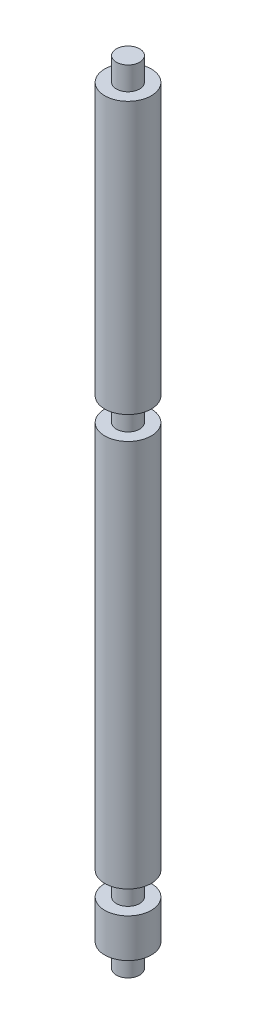
SolidWorks part; units mm, degrees
material "Cast Alloy Steel"
ref_plane "Front Plane" through (0, 0, 0) normal (0, 0, 1) x (1, 0, 0)
ref_plane "Top Plane" through (0, 0, 0) normal (0, 1, 0) x (1, 0, 0)
ref_plane "Right Plane" through (0, 0, 0) normal (1, 0, 0) x (0, 0, -1)
sketch "Sketch1" plane through (0, 0, 0) normal (1, 0, 0) x (0, 0, -1)
  line L0 (0, 102) -> (1.5, 102)
  line L1 (1.5, 102) -> (1.5, 99)
  line L2 (1.5, 99) -> (3, 99)
  line L3 (3, 99) -> (3, 64)
  line L4 (3, 64) -> (1.5, 64)
  line L5 (1.5, 64) -> (1.5, 61)
  line L6 (1.5, 61) -> (3, 61)
  line L7 (3, 61) -> (3, 11)
  line L8 (3, 11) -> (1.5, 11)
  line L9 (1.5, 11) -> (1.5, 8)
  line L10 (1.5, 8) -> (3, 8)
  line L11 (3, 8) -> (3, 3)
  line L12 (3, 3) -> (1.5, 3)
  line L13 (1.5, 3) -> (1.5, 0)
  line L14 (1.5, 0) -> (0, 0)
  line L15 (0, 0) -> (0, 102)
  dimension "D1" = 3
  dimension "D2" = 1.5
  dimension "D3" = 3
  dimension "D4" = 3
  dimension "D5" = 5
  dimension "D6" = 50
  dimension "D7" = 35
revolve "Revolve1" add sketch "Sketch1" angle 360 about L15
